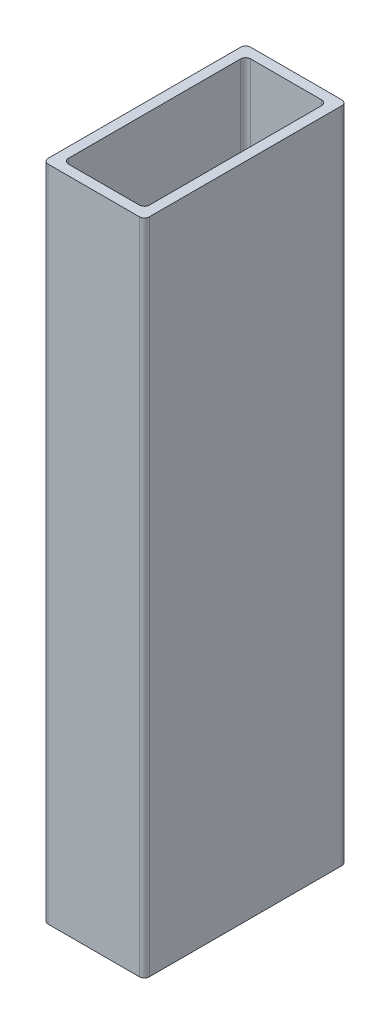
SolidWorks part; units mm, degrees
ref_plane "Plan de face" through (0, 0, 0) normal (0, 0, 1) x (1, 0, 0)
ref_plane "Plan de dessus" through (0, 0, 0) normal (0, 1, 0) x (1, 0, 0)
ref_plane "Plan de droite" through (0, 0, 0) normal (1, 0, 0) x (0, 0, -1)
sketch "Esquisse2" plane through (0, 0, 0) normal (0, 1, 0) x (1, 0, 0)
  line L0 (6, 4) -> (34, 4)
  line L1 (2, 0) -> (38, 0)
  line L2 (0, 2) -> (0, 78)
  line L3 (2, 80) -> (38, 80)
  line L4 (40, 2) -> (40, 78)
  line L5 (36, 6) -> (36, 74)
  line L6 (6, 76) -> (34, 76)
  line L7 (4, 6) -> (4, 74)
  line L8 (4, 4) -> (36, 4) construction
  line L9 (36, 4) -> (36, 76) construction
  line L10 (4, 76) -> (36, 76) construction
  line L11 (4, 4) -> (4, 76) construction
  line L12 (0, 0) -> (40, 0) construction
  line L13 (0, 0) -> (0, 80) construction
  line L14 (0, 80) -> (40, 80) construction
  line L15 (40, 0) -> (40, 80) construction
  arc A0 (34, 4) -> (36, 6) centre (34, 6) ccw
  arc A1 (36, 74) -> (34, 76) centre (34, 74) ccw
  arc A2 (6, 76) -> (4, 74) centre (6, 74) ccw
  arc A3 (4, 6) -> (6, 4) centre (6, 6) ccw
  arc A4 (2, 0) -> (0, 2) centre (2, 2) cw
  arc A5 (0, 78) -> (2, 80) centre (2, 78) cw
  arc A6 (38, 80) -> (40, 78) centre (38, 78) cw
  arc A7 (40, 2) -> (38, 0) centre (38, 2) cw
  point P24 (0, 0)
  dimension "D4" = 2
  dimension "D1" = 80
  dimension "D2" = 40
  dimension "D3" = 4
extrude "Boss.-Extru.1" add sketch "Esquisse2" along normal blind 260
